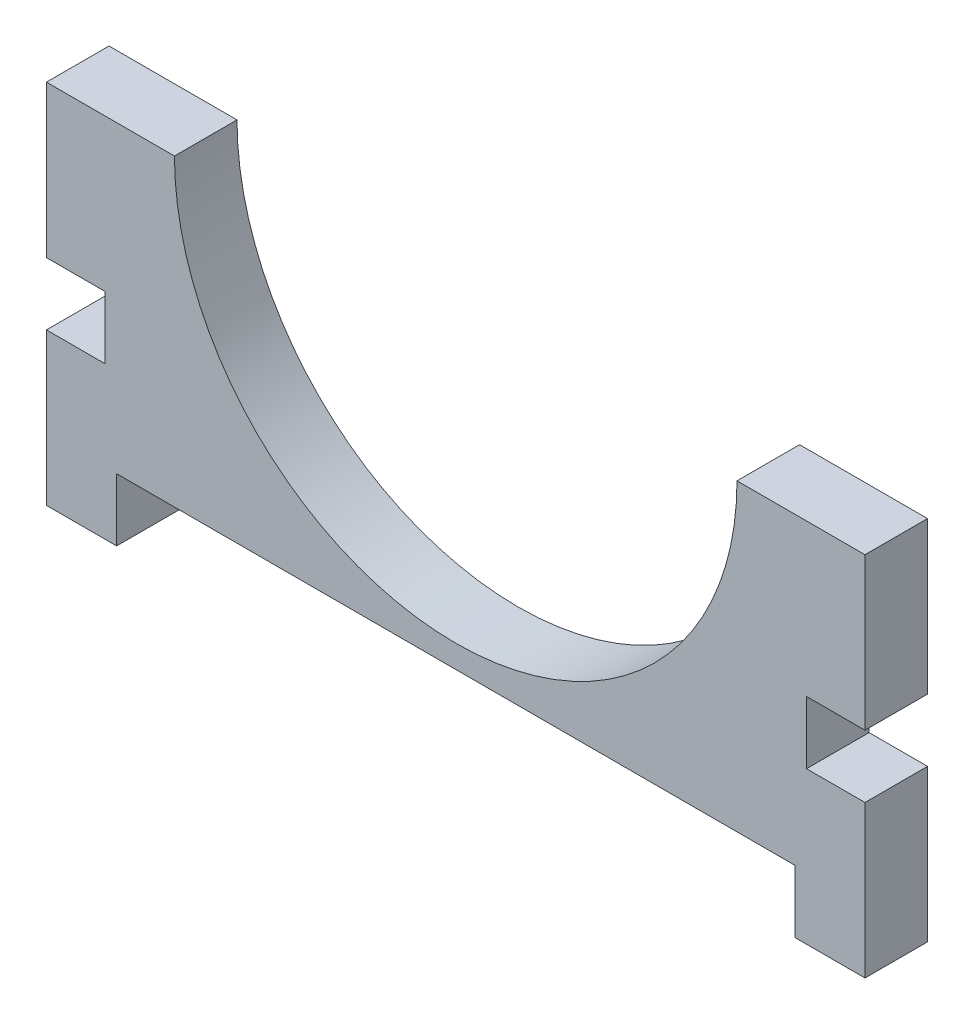
SolidWorks part; units mm, degrees
ref_plane "Front Plane" through (0, 0, 0) normal (0, 0, 1) x (1, 0, 0)
ref_plane "Top Plane" through (0, 0, 0) normal (0, 1, 0) x (1, 0, 0)
ref_plane "Right Plane" through (0, 0, 0) normal (1, 0, 0) x (0, 0, -1)
sketch "Model" plane through (0, 0, 0) normal (0, 0, 1) x (1, 0, 0)
  line L18 (0, 0) -> (0, 26) construction
  line L19 (-29, 0) -> (29, 0)
  line L20 (-35, -0.7845) -> (-35, 7.65)
  line L21 (-35, 26) -> (-24.055, 26)
  line L22 (35, -0.7845) -> (35, 7.65)
  line L23 (35, -5.35) -> (29, -5.35)
  line L24 (24.055, 26) -> (35, 26)
  line L25 (-35, -0.7845) -> (-35, -5.35)
  line L26 (-35, -5.35) -> (-29, -5.35)
  line L27 (-29, 0) -> (-29, -5.35)
  line L28 (29, 0) -> (29, -5.35)
  line L30 (35, -0.7845) -> (35, -5.35)
  line L31 (35, 7.65) -> (30, 7.65)
  line L32 (-35, 13) -> (-30, 13)
  line L33 (35, 13) -> (35, 26)
  line L34 (-35, 7.65) -> (-30, 7.65)
  line L35 (-30, 13) -> (-30, 7.65)
  line L36 (30, 13) -> (30, 7.65)
  line L37 (35, 13) -> (30, 13)
  line L39 (-35, 13) -> (-35, 26)
  arc A1 (-24.055, 26) -> (24.055, 26) centre (0, 26) ccw
  point P43 (0, 26)
  dimension "D18" = 24.055
  dimension "D11" = 5
  dimension "D12" = 6
  dimension "D13" = 5.35
  dimension "D14" = 5.35
  dimension "D15" = 13
  dimension "D16" = 26
  dimension "D17" = 70
extrude "Boss-Extrude1" add sketch "Model" along normal blind 5.35
equation "\"mdfthick\"=5.35"
equation "\"D13@Model\"=\"mdfthick\""
equation "\"D14@Model\"=\"mdfthick\""
equation "\"D1@Boss-Extrude1\"=\"mdfthick\""
